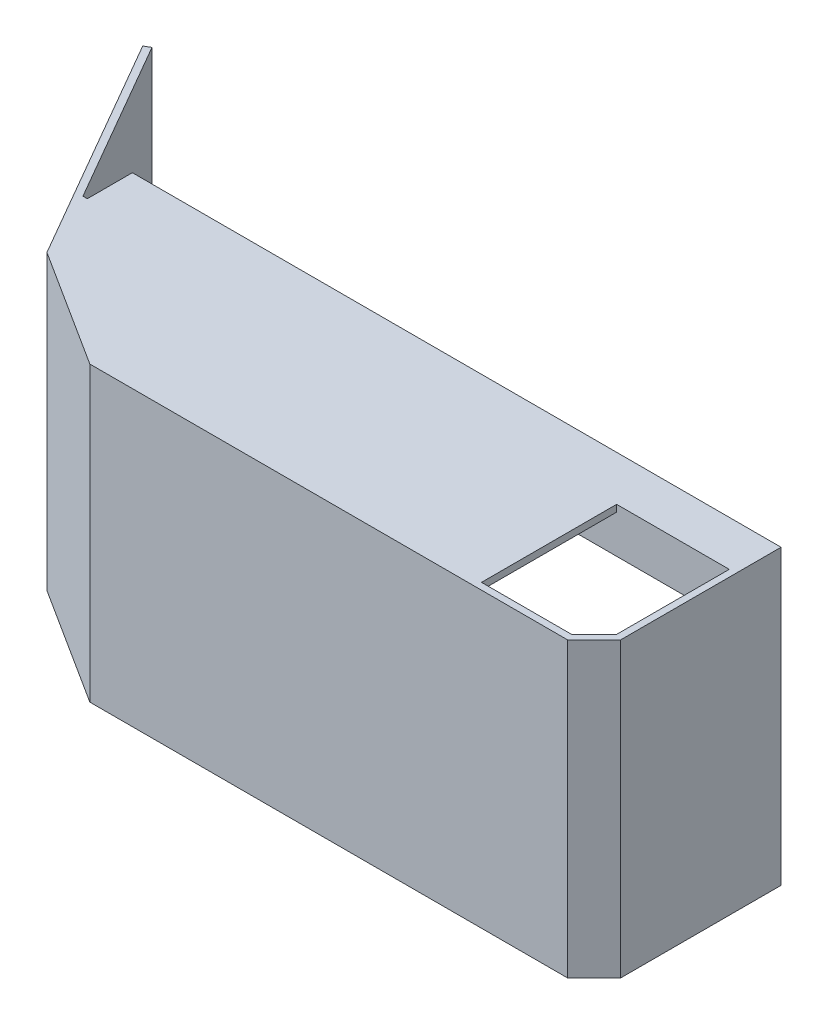
SolidWorks part; units mm, degrees
ref_plane "Front Plane" through (0, 0, 0) normal (0, 0, 1) x (1, 0, 0)
ref_plane "Top Plane" through (0, 0, 0) normal (0, 1, 0) x (1, 0, 0)
ref_plane "Right Plane" through (0, 0, 0) normal (1, 0, 0) x (0, 0, -1)
sketch "Sketch1" plane through (0, 0, 0) normal (0, 0, 1) x (1, 0, 0)
  line L1 (-142.5, -65) -> (142.5, -65)
  line L2 (-142.5, -65) -> (-142.5, 65)
  line L3 (-142.5, 65) -> (142.5, 65)
  line L4 (142.5, -65) -> (142.5, 65)
  line L5 (-142.5, -65) -> (142.5, 65) construction
  line L6 (-142.5, 65) -> (142.5, -65) construction
  line L7 (-122.5, -45) -> (122.5, -45)
  line L8 (-122.5, -45) -> (-122.5, 45)
  line L9 (-122.5, 45) -> (122.5, 45)
  line L10 (122.5, -45) -> (122.5, 45)
  line L11 (-122.5, -45) -> (122.5, 45) construction
  line L12 (-122.5, 45) -> (122.5, -45) construction
  point P0 (0, 0)
  point P6 (0, 0)
  dimension "D1" = 285
  dimension "D2" = 20
  dimension "D3" = 130
  dimension "D4" = 20
extrude "Boss-Extrude1" add sketch "Sketch1" along normal blind 20
sketch "Sketch2" plane through (0, 65, 0) normal (0, 1, 0) x (1, 0, 0)
  line L0 (-186.3168, 52.5206) -> (-128.5817, -47.4794)
  line L1 (-228.1865, 125.0411) -> (-144.447, -20) construction
  line L2 (-128.5817, -47.4794) -> (-77.5, -80)
  line L3 (-77.5, -80) -> (132.5, -80)
  line L4 (142.5, -70) -> (142.5, 0)
  line L5 (142.5, 0) -> (-142.5, 0) construction
  line L6 (132.5, -80) -> (142.5, -70)
  point P5 (142.5, -80)
  point P8 (-143.2818, -60.8864)
  point P11 (-186.3168, 52.5206)
  dimension "D1" = 80
  dimension "D2" = 100
  dimension "D3" = 220
extrude "Extrude-Thin1" add sketch "Sketch2" against normal through all thin
sketch "Sketch3" plane through (142.5, 0, 0) normal (-1, 0, 0) x (0, 0, 1)
  line L0 (70, 65) -> (20, 65) construction
  line L1 (80, -65) -> (20, -65)
  line L2 (80, -65) -> (80, -62)
  line L3 (80, -62) -> (20, -62)
  line L4 (20, -65) -> (20, -62)
  line L5 (80, 65) -> (20, 65)
  line L6 (80, 65) -> (80, 62)
  line L7 (80, 62) -> (20, 62)
  line L8 (20, 65) -> (20, 62)
  line L9 (20, -65) -> (20, 65) construction
  point P10 (37.5486, 65)
  point P13 (0, 0)
  point P16 (0, 0)
  dimension "D1" = 3
  dimension "D2" = 3
extrude "Boss-Extrude2" add sketch "Sketch3" along normal up to next from offset 50 separate body
